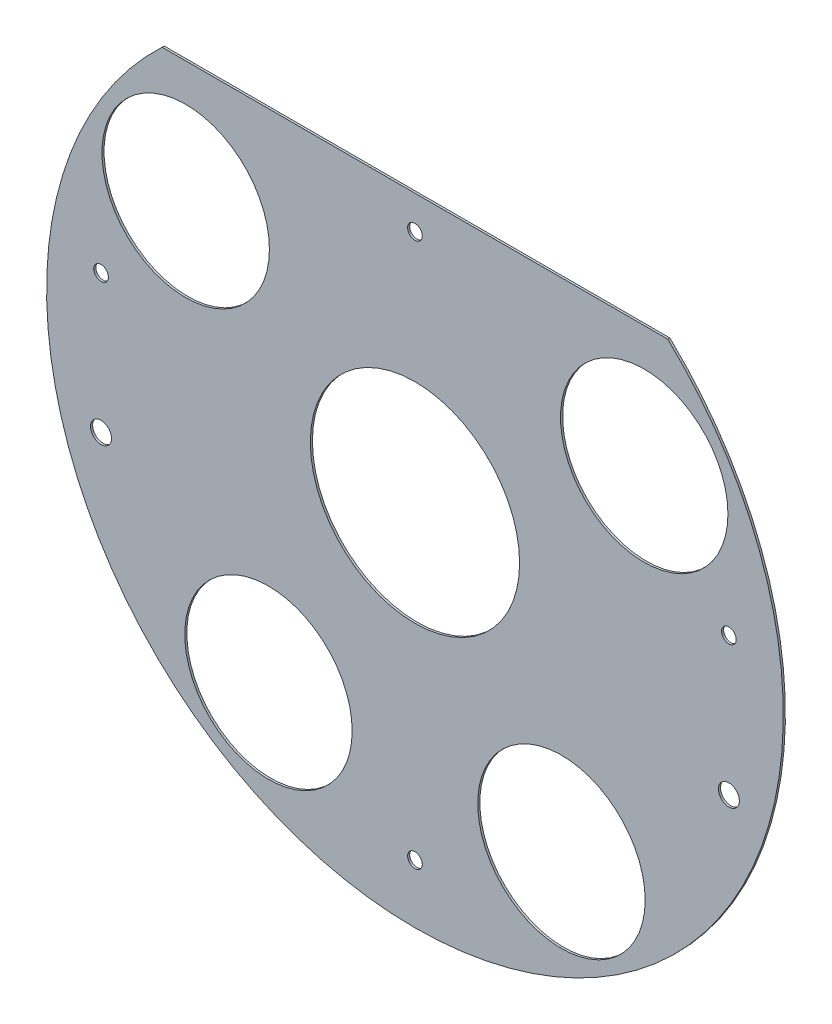
SolidWorks part; units mm, degrees
material "尼龙 101"
ref_plane "前视基准面" through (0, 0, 0) normal (0, 0, 1) x (1, 0, 0)
ref_plane "上视基准面" through (0, 0, 0) normal (0, 1, 0) x (1, 0, 0)
ref_plane "右视基准面" through (0, 0, 0) normal (1, 0, 0) x (0, 0, -1)
sketch "Sketch1" plane through (0, 0, 0) normal (0, 0, 1) x (1, 0, 0)
  line L0 (-60.3987, 64) -> (60.3987, 64)
  arc A0 (-60.3987, 64) -> (60.3987, 64) centre (0, 0) ccw
  circle A1 centre (0, 0) radius 25
  circle A2 centre (-35, -54.7723) radius 20
  circle A3 centre (-54.7723, 35) radius 20
  circle A4 centre (54.7723, 35) radius 20
  circle A5 centre (35, -54.7723) radius 20
  circle A6 centre (0, 0) radius 65 construction
  circle A7 centre (-75, 10) radius 1.75
  circle A8 centre (0, 56) radius 1.75
  circle A9 centre (0, -74) radius 1.75
  circle A10 centre (75, 10) radius 1.75
  circle A11 centre (-75, -23) radius 2.5
  circle A12 centre (75, -23) radius 2.5
  dimension "D1" = 176
  dimension "D3" = 50
  dimension "D4" = 35
  dimension "D5" = 40
  dimension "D6" = 40
  dimension "D7" = 35
  dimension "D11" = 130
  dimension "D8" = 40
  dimension "D9" = 40
  dimension "D10" = 3.5
  dimension "D12" = 3.5
  dimension "D13" = 3.5
  dimension "D18" = 3.5
  dimension "D20" = 5
  dimension "D22" = 5
  dimension "D2" = 64
  dimension "D14" = 56
  dimension "D15" = 74
  dimension "D16" = 75
  dimension "D17" = 10
  dimension "D19" = 150
  dimension "D21" = 23
  dimension "D23" = 150
extrude "Extrude1" add sketch "Sketch1" along normal blind 0.5
